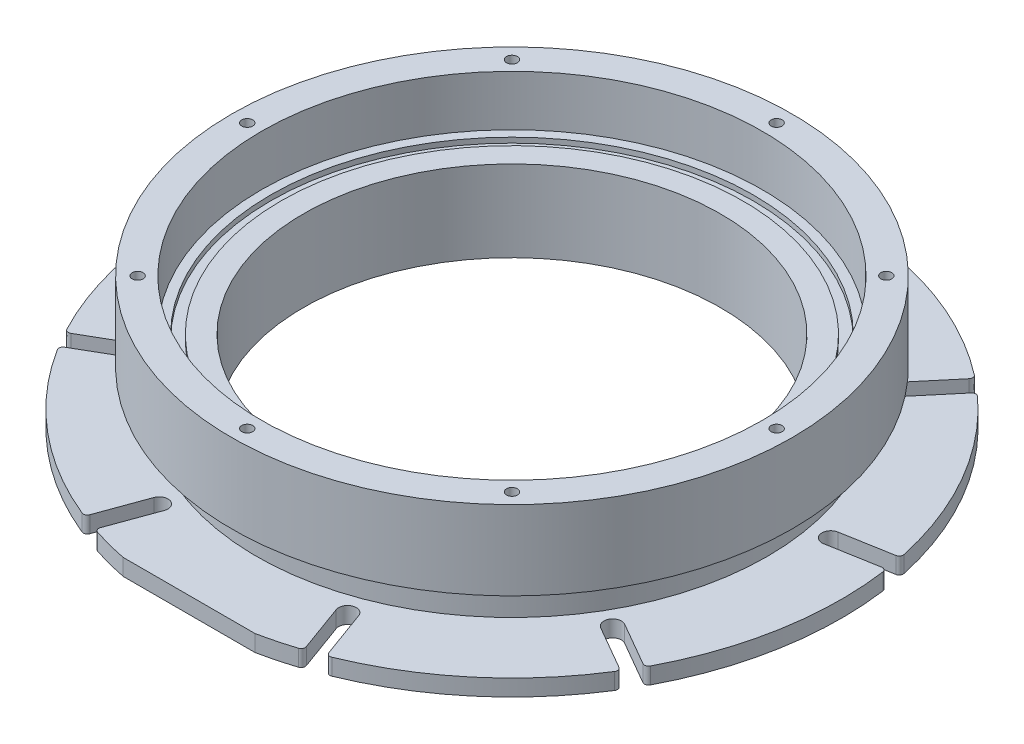
SolidWorks part; units mm, degrees
material "AISI 304"
ref_plane "Front" through (0, 0, 0) normal (0, 0, 1) x (1, 0, 0)
ref_plane "Top" through (0, 0, 0) normal (0, 1, 0) x (1, 0, 0)
ref_plane "Right" through (0, 0, 0) normal (1, 0, 0) x (0, 0, -1)
sketch "Sketch1" plane through (0, 0, 0) normal (0, 0, 1) x (1, 0, 0)
  line L0 (0, 0) -> (0, 50.8) construction
  line L2 (80.3783, 0) -> (127, 0)
  line L3 (127, 0) -> (127, 6.35)
  line L4 (108, 50.8) -> (96.5, 50.8)
  line L8 (80.3783, 31.3) -> (80.3783, 0)
  line L9 (80.3783, 31.3) -> (96.5, 31.3)
  line L10 (96.5, 31.3) -> (96.5, 50.8)
  line L11 (108, 50.8) -> (108, 20.32)
  line L12 (98.425, 6.35) -> (127, 6.35)
  line L14 (108, 20.32) -> (98.425, 20.32)
  line L15 (98.425, 20.32) -> (98.425, 6.35)
  dimension "D1" = 160.7566
  dimension "D2" = 254
  dimension "D3" = 19.5
  dimension "D4" = 50.8
  dimension "D5" = 193
  dimension "D6" = 216
  dimension "D7" = 6.35
  dimension "D8" = 13.97
  dimension "D9" = 196.85
revolve "Revolve1" add sketch "Sketch1" angle 360 about L0
hole_wizard "M5x0.8 Tapped Hole1" positions "Sketch2" profile "Sketch3" tap size "M5x0.8" standard "ANSI Metric"
sketch "Sketch2" plane through (0, 50.8, 0) normal (0, 1, 0) x (1, 0, 0)
  line L0 (0, 0) -> (0, 102) construction
  point P0 (0, 102)
  point P6 (72.1249, 72.1249)
  point P7 (102, 0)
  point P8 (72.1249, -72.1249)
  point P9 (0, -102)
  point P10 (-72.1249, -72.1249)
  point P11 (-102, 0)
  point P12 (-72.1249, 72.1249)
  dimension "D2" = 102
  dimension "D1" = 8
sketch "Sketch3" plane through (0, 50.8, -102) normal (1, 0, 0) x (0, 0, 1)
  line L0 (0, 0) -> (0, 18.6608)
  line L1 (0, 18.6608) -> (2.1, 17.399)
  line L2 (2.1, 17.399) -> (2.1, 0)
  line L5 (2.1, 0) -> (0, 0)
  line L10 (0, 18.6608) -> (-2.1, 17.399) construction
  line L11 (0, -6.35) -> (0, 107.95) construction
  dimension "Tap Drill Dia." = 4.2
  dimension "Tap Drill Depth" = 17.399
  dimension "Drill Angle" = 118
cosmetic thread "Hole Thread1" parameters "D1"=15, "D2"=5.2
cosmetic thread "Hole Thread2" parameters "D1"=15, "D2"=5.2
cosmetic thread "Hole Thread3" parameters "D1"=15, "D2"=5.2
cosmetic thread "Hole Thread4" parameters "D1"=15, "D2"=5.2
cosmetic thread "Hole Thread5" parameters "D1"=15, "D2"=5.2
cosmetic thread "Hole Thread6" parameters "D1"=15, "D2"=5.2
cosmetic thread "Hole Thread7" parameters "D1"=15, "D2"=5.2
cosmetic thread "Hole Thread8" parameters "D1"=15, "D2"=5.2
sketch "Sketch7" plane through (0, 50.8, 0) normal (0, 1, 0) x (1, 0, 0)
  line L1 (-25.4, -124.4341) -> (25.4, -124.4341)
  line L2 (-25.4, -124.4341) -> (-25.4, -127)
  line L3 (-25.4, -127) -> (25.4, -127)
  line L4 (25.4, -124.4341) -> (25.4, -127)
  circle A0 centre (0, 0) radius 127 construction
  dimension "D1" = 50.8
extrude "Cut-Extrude1" cut sketch "Sketch7" against normal up to next
sketch "Sketch10" plane through (0, 0, 0) normal (0, -1, 0) x (1, 0, 0)
  line L0 (0, -106.045) -> (0, 0) construction
  line L2 (-3.3782, -106.045) -> (-3.3782, -127)
  line L3 (-3.3782, -127) -> (3.3782, -127)
  line L4 (3.3782, -106.045) -> (3.3782, -127)
  arc A0 (-3.3782, -106.045) -> (3.3782, -106.045) centre (0, -106.045) cw
  arc A1 (-25.4, 124.4341) -> (25.4, 124.4341) centre (0, 0) ccw construction
  circle A2 centre (0, 0) radius 98.425 construction
  circle A3 centre (0, 0) radius 98.425 construction
  circle A4 centre (0, -106.045) radius 4.7625 construction
  dimension "D1" = 106.045
  dimension "D2" = 3.3782
  dimension "D3" = 2.8575
  dimension "D4" = 9.525
extrude "Cut-Extrude2" cut sketch "Sketch10" against normal up to next
fillet "Fillet1" radius 1.5875 2 edges at (-3.3782, 3.175, -126.9551) (3.3782, 3.175, -126.9551)
pattern_circular "CirPattern1" count 9 over 360 about axis through (0, 0, 0) along (0, 1, 0) of "Cut-Extrude2", "Fillet1"
sketch "Sketch11" plane through (0, 31.3, 0) normal (0, 1, 0) x (1, 0, 0)
  circle A0 centre (0, 0) radius 89
  circle A1 centre (0, 0) radius 93
  dimension "D1" = 178
  dimension "D2" = 186
extrude "Cut-Extrude3" cut sketch "Sketch11" against normal blind 2
